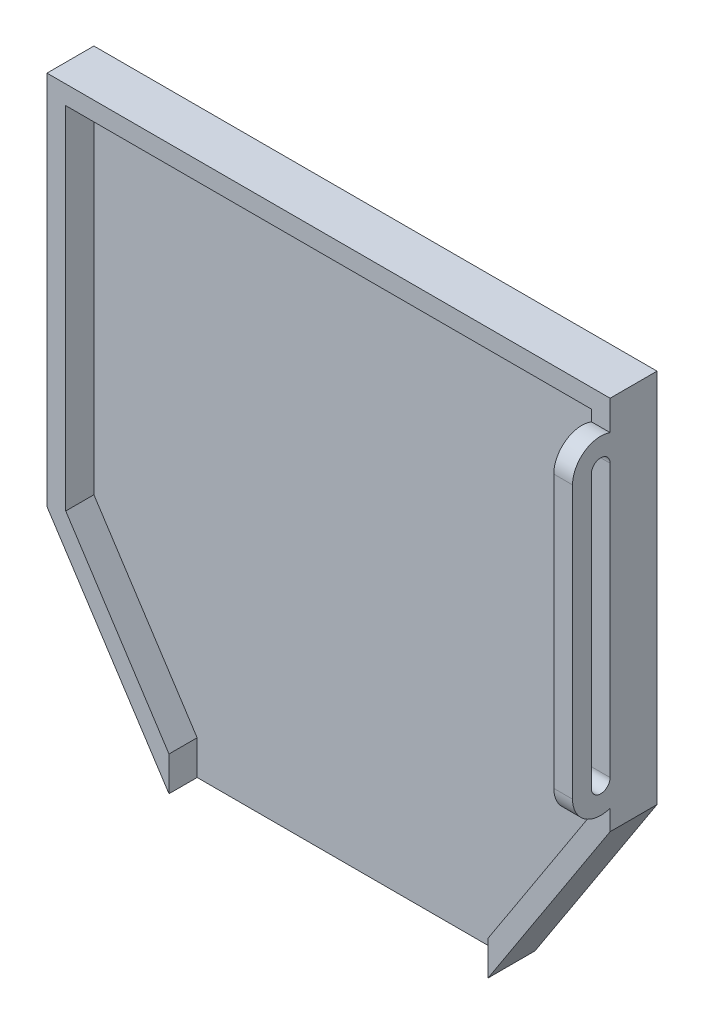
SolidWorks part; units mm, degrees
ref_plane "Přední rovina" through (0, 0, 0) normal (0, 0, 1) x (1, 0, 0)
ref_plane "Horní rovina" through (0, 0, 0) normal (0, 1, 0) x (1, 0, 0)
ref_plane "Pravá rovina" through (0, 0, 0) normal (1, 0, 0) x (0, 0, -1)
sketch "Skica1" plane through (0, 0, 0) normal (0, 0, 1) x (1, 0, 0)
  line L0 (0, 0) -> (34, 0)
  line L1 (34, 0) -> (47, 20)
  line L2 (47, 20) -> (47, 60)
  line L3 (47, 60) -> (-13, 60)
  line L4 (-13, 60) -> (-13, 20)
  line L5 (-13, 20) -> (0, 0)
  point P2 (17, 60)
  point P8 (17, 0)
  dimension "D1" = 34
  dimension "D2" = 60
  dimension "D3" = 20
  dimension "D4" = 60
extrude "Přidat vysunutím1" add sketch "Skica1" along normal blind 2
sketch "Skica2" plane through (0, 0, 2) normal (0, 0, 1) x (1, 0, 0)
  line L0 (-11, 20.5929) -> (0, 3.6698)
  line L2 (34, 3.6698) -> (45, 20.5929)
  line L3 (45, 20.5929) -> (45, 58)
  line L4 (45, 58) -> (-11, 58)
  line L5 (-11, 58) -> (-11, 20.5929)
  line L6 (-13, 20) -> (0, 0)
  line L7 (0, 0) -> (34, 0)
  line L8 (34, 0) -> (47, 20)
  line L9 (47, 20) -> (47, 60)
  line L10 (47, 60) -> (-13, 60)
  line L11 (-13, 60) -> (-13, 20)
  line L12 (-13, 20) -> (0, 0)
  line L14 (34, 0) -> (47, 20)
  line L15 (47, 20) -> (47, 60)
  line L16 (47, 60) -> (-13, 60)
  line L17 (-13, 60) -> (-13, 20)
  line L19 (-11, 20.5929) -> (1.0854, 2) construction
  line L20 (0, 0) -> (0, 3.6698)
  line L21 (34, 0) -> (34, 3.6698)
  line L22 (0, 0) -> (34, 0) construction
  line L23 (1.0854, 2) -> (32.9146, 2) construction
  line L24 (32.9146, 2) -> (45, 20.5929) construction
  dimension "D1" = 0
  dimension "D2" = 2
extrude "Přidat vysunutím2" add sketch "Skica2" along normal blind 3
sketch "Skica3" plane through (47, 0, 0) normal (1, 0, 0) x (0, 0, -1)
  line L0 (-6, 25) -> (-6, 54) construction
  line L1 (-7, 25) -> (-7, 54)
  line L2 (-5, 25) -> (-5, 54)
  line L3 (-5, 20) -> (-5, 60) construction
  line L4 (-5, 60) -> (0, 60) construction
  line L5 (-9, 25) -> (-9, 54)
  line L7 (-5, 22.1716) -> (-5, 56.8284)
  line L10 (-3, 25) -> (-3, 54) construction
  arc A0 (-7, 25) -> (-5, 25) centre (-6, 25) ccw
  arc A1 (-5, 54) -> (-7, 54) centre (-6, 54) ccw
  arc A2 (-5, 56.8284) -> (-9, 54) centre (-6, 54) ccw
  arc A3 (-9, 25) -> (-5, 22.1716) centre (-6, 25) ccw
  arc A4 (-9, 25) -> (-3, 25) centre (-6, 25) ccw construction
  arc A5 (-3, 54) -> (-9, 54) centre (-6, 54) ccw construction
  point P2 (-6, 39.5)
  line M12 (-5, 60) -> (-5, 20)
  dimension "D1" = 1
  dimension "D2" = 29
  dimension "D3" = 6
  dimension "D4" = 2
extrude "Přidat vysunutím3" add sketch "Skica3" against normal blind 2 contours L5 A3 A0 L1 A1 A2 M12
